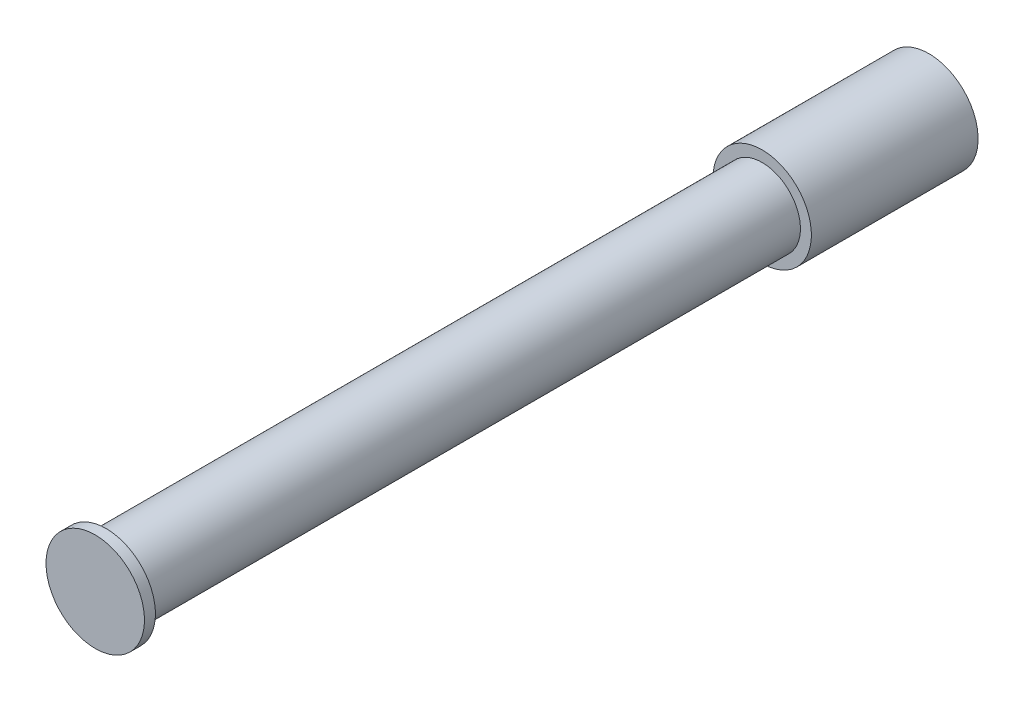
SolidWorks part; units mm, degrees
material "Copper"
ref_plane "Front Plane" through (0, 0, 0) normal (0, 0, 1) x (1, 0, 0)
ref_plane "Top Plane" through (0, 0, 0) normal (0, 1, 0) x (1, 0, 0)
ref_plane "Right Plane" through (0, 0, 0) normal (1, 0, 0) x (0, 0, -1)
sketch "Sketch1" plane through (0, 0, 0) normal (0, 0, 1) x (1, 0, 0)
  circle A2 centre (0, 5.8264) radius 2.25
  circle A3 centre (0, 5.8264) radius 2.25
  dimension "D1" = 0.5
extrude "Boss-Extrude1" add sketch "Sketch1" along normal blind 38.1
sketch "Sketch3" plane through (0, 0, 0) normal (0, 0, -1) x (-1, 0, 0)
  circle A0 centre (0, 5.8264) radius 1.75 construction
  circle A1 centre (0, 5.8264) radius 1.75
extrude "Cut-Extrude1" cut sketch "Sketch3" against normal blind 29.98 from offset 7.62 flip side to cut offset against normal yes
